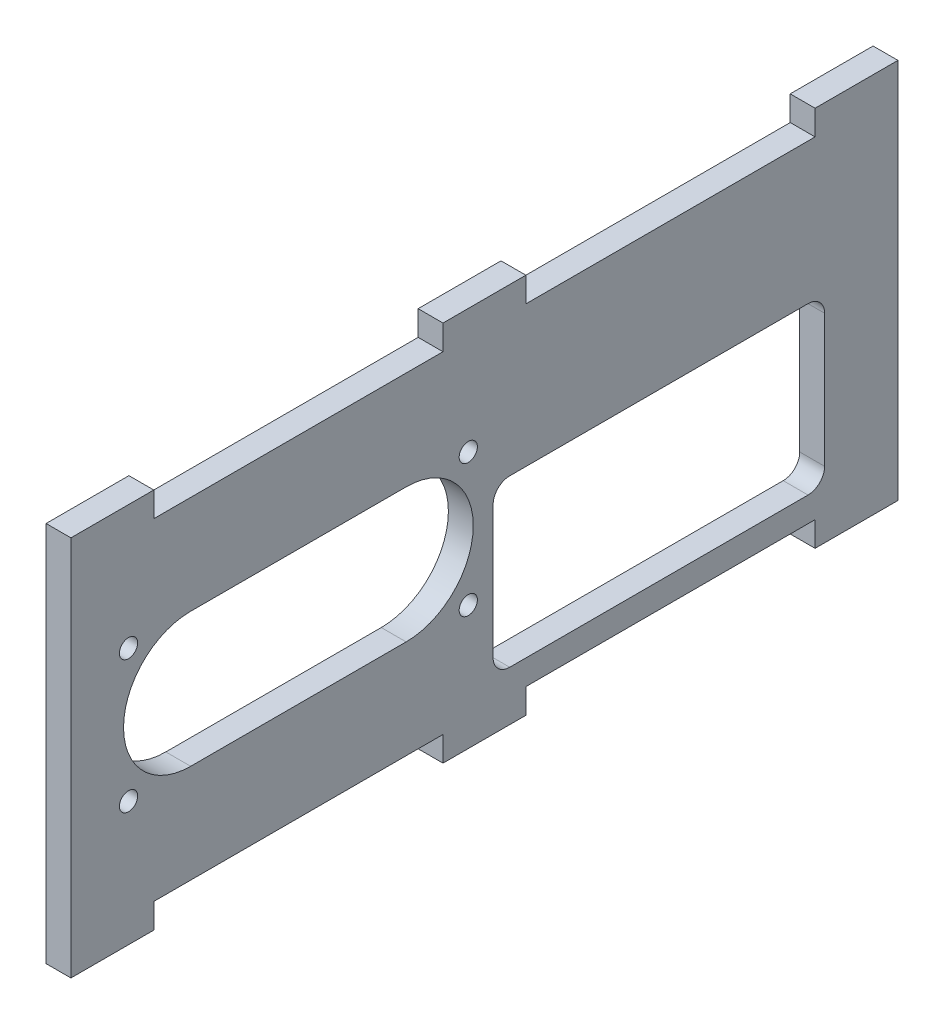
SolidWorks part; units mm, degrees
ref_plane "Front Plane" through (0, 0, 0) normal (0, 0, 1) x (1, 0, 0)
ref_plane "Top Plane" through (0, 0, 0) normal (0, 1, 0) x (1, 0, 0)
ref_plane "Right Plane" through (0, 0, 0) normal (1, 0, 0) x (0, 0, -1)
sketch "Sketch1" plane through (0, 0, 0) normal (1, 0, 0) x (0, 0, -1)
  line L0 (17.45, 20) -> (17.45, 23)
  line L1 (-27.45, 20) -> (72.35, 20)
  line L2 (-27.45, 20) -> (-27.45, -20)
  line L3 (-27.45, -20) -> (72.35, -20)
  line L4 (72.35, 20) -> (72.35, -20)
  line L5 (-27.45, 20) -> (-17.45, 20)
  line L6 (-27.45, 20) -> (-27.45, 23)
  line L7 (-27.45, 23) -> (-17.45, 23)
  line L8 (-17.45, 20) -> (-17.45, 23)
  line L9 (17.45, 20) -> (27.45, 20)
  line L10 (27.45, 20) -> (27.45, 23)
  line L11 (17.45, 23) -> (27.45, 23)
  line L12 (62.35, 20) -> (62.35, 23)
  line L13 (62.35, 20) -> (72.35, 20)
  line L14 (72.35, 20) -> (72.35, 23)
  line L15 (62.35, 23) -> (72.35, 23)
  line L16 (-17.45, 23) -> (17.45, 23) construction
  line L17 (27.45, 23) -> (62.35, 23) construction
  line L18 (-27.45, 0) -> (72.35, 0) construction
  line L19 (62.35, -20) -> (72.35, -20)
  line L20 (72.35, -20) -> (72.35, -23)
  line L21 (62.35, -23) -> (72.35, -23)
  line L22 (62.35, -20) -> (62.35, -23)
  line L23 (17.45, -20) -> (27.45, -20)
  line L24 (27.45, -20) -> (27.45, -23)
  line L25 (17.45, -23) -> (27.45, -23)
  line L26 (17.45, -20) -> (17.45, -23)
  line L27 (-27.45, -23) -> (-17.45, -23)
  line L28 (-17.45, -20) -> (-17.45, -23)
  line L29 (-27.45, -20) -> (-17.45, -20)
  line L30 (-27.45, -20) -> (-27.45, -23)
  point P7 (0, 23)
  point P8 (-27.45, 0)
  point P30 (-22.45, 23)
  point P31 (22.45, 23)
  dimension "D1" = 10
  dimension "D2" = 3
  dimension "D4" = 44.9
  dimension "D5" = 40
  dimension "D3" = 3
extrude "Boss-Extrude1" add sketch "Sketch1" along normal blind 3 contours L4 L1 L2 L3 | L1 L8 L7 L6 | L11 L0 L1 L10 | L15 L12 L1 L14 | L3 L22 L21 L20 | L3 L26 L25 L24 | L3 L30 L27 L28
sketch "Sketch2" plane through (3, 0, 0) normal (1, 0, 0) x (0, 0, -1)
  line L0 (22.45, 23) -> (22.45, -23) construction
  line L1 (17.45, 23) -> (27.45, 23) construction
  line L2 (17.45, -23) -> (27.45, -23) construction
  line L3 (-22.45, 23) -> (-22.45, -23) construction
  line L4 (-27.45, 23) -> (-17.45, 23) construction
  line L5 (-27.45, -23) -> (-17.45, -23) construction
  line L6 (-22.45, 0) -> (22.45, 0) construction
  point P14 (0, 0)
  line B0 (-13, 8.1) -> (13, 8.1)
  line B1 (-13, -8.1) -> (13, -8.1)
  arc B2 (-13, 8.1) -> (-13, -8.1) centre (-13, 0) ccw
  arc B3 (13, -8.1) -> (13, 8.1) centre (13, 0) ccw
  circle B4 centre (-20.5, 8) radius 1.1
  circle B5 centre (-20.5, -8) radius 1.1
  circle B6 centre (20.5, 8) radius 1.1
  circle B7 centre (20.5, -8) radius 1.1
sketch_block_instance "Block-SRF05-1"
sketch_block "Block-SRF05" parameters "D4"=16.2, "D5"=2.2, "D1"=45, "D2"=20, "D3"=26, "D6"=2, "D7"=2, "D8"=2, "D9"=2
extrude "Cut-Extrude1" cut sketch "Sketch2" against normal through all
sketch "Sketch3" plane through (3, 0, 0) normal (1, 0, 0) x (0, 0, -1)
  line L0 (27.45, -20) -> (62.35, -20) construction
  line L1 (23.5, 3) -> (63.5, 3)
  line L2 (23.5, 3) -> (23.5, -17)
  line L3 (23.5, -17) -> (63.5, -17)
  line L4 (63.5, 3) -> (63.5, -17)
  line L5 (22.5, 20) -> (22.5, -20) construction
  line L6 (-17.45, 20) -> (17.45, 20) construction
  line L7 (-17.45, -20) -> (17.45, -20) construction
  point P12 (20.5, -8)
  dimension "D1" = 3
  dimension "D2" = 2
  dimension "D3" = 40
  dimension "D4" = 20
  dimension "D5" = 1
extrude "Cut-Extrude2" cut sketch "Sketch3" against normal through all
fillet "Fillet1" radius 2 4 edges at (1.5, -17, -23.5) (1.5, -17, -63.5) (1.5, 3, -63.5) (1.5, 3, -23.5)
